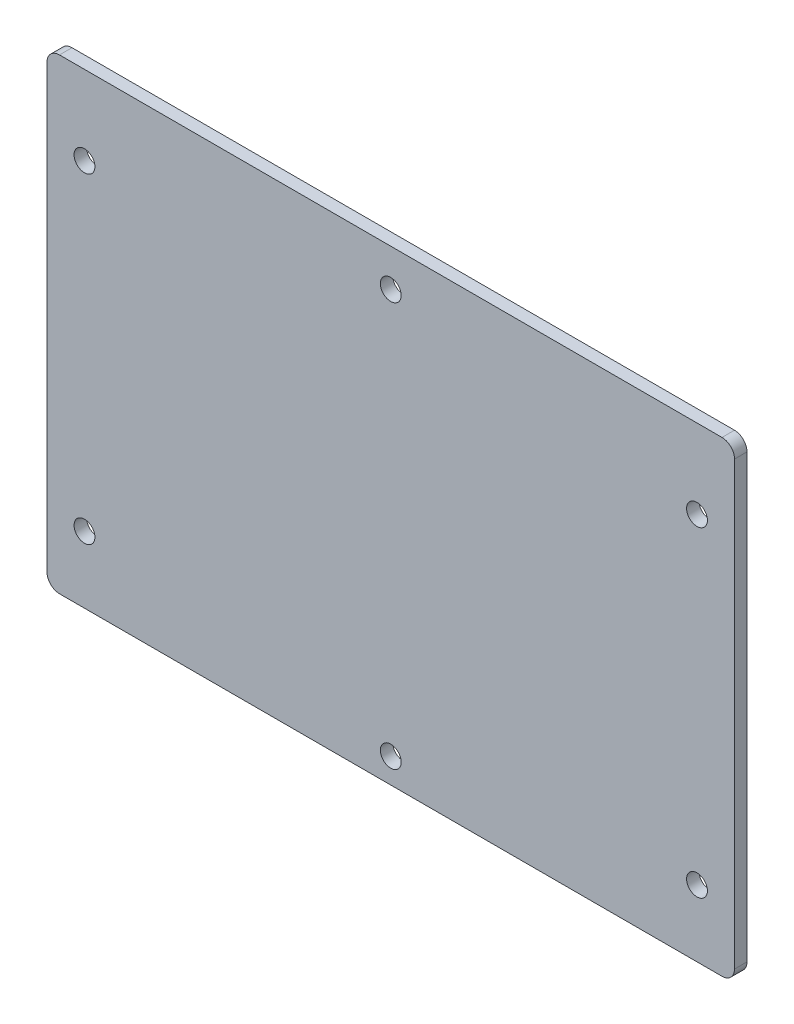
SolidWorks part; units mm, degrees
material "1.0420 (G200)"
ref_plane "正面" through (0, 0, 0) normal (0, 0, 1) x (1, 0, 0)
ref_plane "平面" through (0, 0, 0) normal (0, 1, 0) x (1, 0, 0)
ref_plane "右側面" through (0, 0, 0) normal (1, 0, 0) x (0, 0, -1)
sketch "ｽｹｯﾁ1" plane through (0, 0, 0) normal (0, 0, 1) x (1, 0, 0)
  line L0 (0, 0) -> (0, 118.0021)
  line L1 (0, 118.0021) -> (165, 118.0021)
  line L2 (165, 118.0021) -> (165, 0)
  line L3 (165, 0) -> (0, 0)
  line L4 (82.5, 118.0021) -> (82.5, 0) construction
  line L5 (0, 60.5011) -> (165, 60.5011) construction
  circle A0 centre (82.5, 109.0021) radius 2.5
  circle A1 centre (9, 99.0021) radius 2.5
  circle A2 centre (9, 22) radius 2.5
  circle A3 centre (82.5, 12) radius 2.5
  circle A4 centre (156, 99.0021) radius 2.5
  circle A5 centre (156, 22) radius 2.5
  point P21 (82.5, 0)
extrude "ﾎﾞｽ - 押し出し1" add sketch "ｽｹｯﾁ1" along normal blind 3
fillet "ﾌｨﾚｯﾄ1" radius 3 4 edges at (165, 0, 1.5) (0, 0, 1.5) (0, 118.0021, 1.5) (165, 118.0021, 1.5)
sketch "ｽｹｯﾁ3" plane through (0, 0, 0) normal (0, 0, -1) x (-1, 0, 0)
  line L0 (-82.5, 0) -> (-82.5, 6)
  line L1 (-3, 0) -> (-162, 0) construction
  line L2 (-82.5, 6) -> (0, 6)
  line L3 (0, 115.0021) -> (0, 3) construction
  line L4 (0, 6) -> (-165, 6)
  line L5 (-165, 3) -> (-165, 115.0021) construction
  line L6 (-165, 6) -> (-165, -4.9294)
  line L7 (-165, -4.9294) -> (0, -5.2327)
  line L8 (0, -5.2327) -> (0, 6)
  line M4 (-165, 115.0021) -> (-165, 3)
  arc M5 (-165, 3) -> (-162, 0) centre (-162, 3) ccw
  line M6 (-162, 0) -> (-3, 0)
  arc M7 (-3, 0) -> (0, 3) centre (-3, 3) ccw
  line M8 (0, 3) -> (0, 115.0021)
extrude "ｶｯﾄ - 押し出し1" cut sketch "ｽｹｯﾁ3" against normal blind 10 contours L0 L4 M4 M5 M6 | L2 L0 M6 M7 M8
fillet "ﾌｨﾚｯﾄ2" radius 3 2 edges at (0, 6, 1.5) (165, 6, 1.5)
